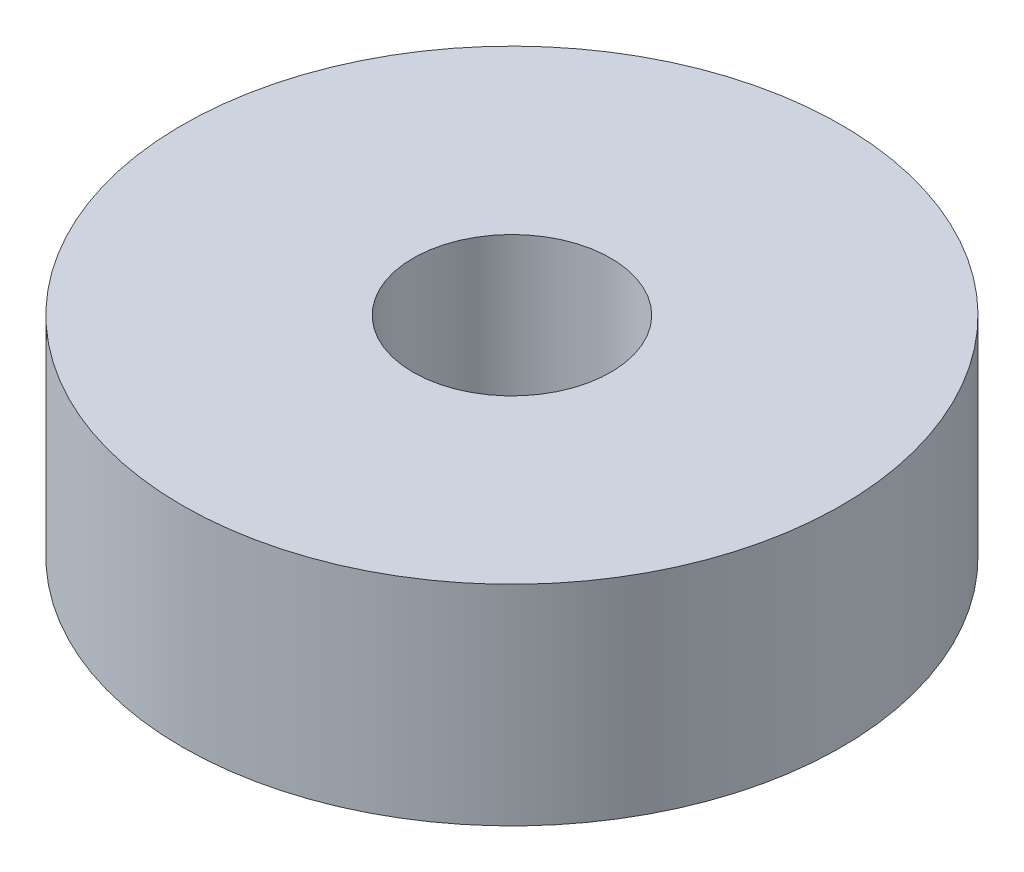
SolidWorks part; units mm, degrees
ref_plane "Front Plane" through (0, 0, 0) normal (0, 0, 1) x (1, 0, 0)
ref_plane "Top Plane" through (0, 0, 0) normal (0, 1, 0) x (1, 0, 0)
ref_plane "Right Plane" through (0, 0, 0) normal (1, 0, 0) x (0, 0, -1)
sketch "Sketch2" plane through (0, 0, 0) normal (0, 1, 0) x (1, 0, 0)
  circle A0 centre (36.2893, 78.2761) radius 1.5
  circle A1 centre (36.2893, 78.2761) radius 5
extrude "Boss-Extrude1" add sketch "Sketch2" along normal blind 3.175
